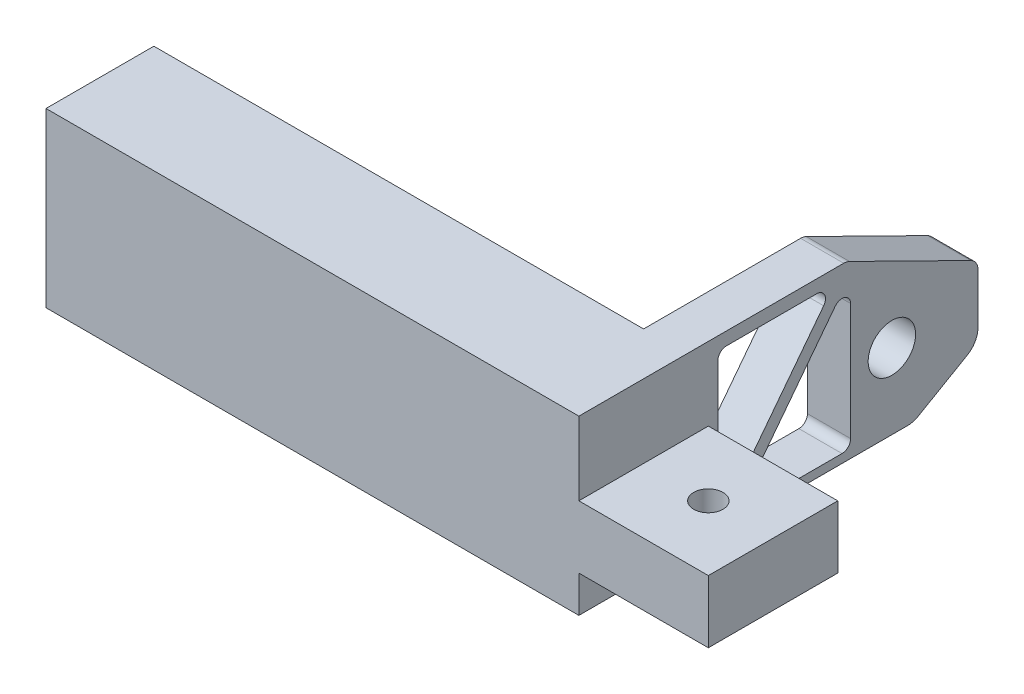
SolidWorks part; units mm, degrees
material "PLA"
ref_plane "Front Plane" through (0, 0, 0) normal (0, 0, 1) x (1, 0, 0)
ref_plane "Top Plane" through (0, 0, 0) normal (0, 1, 0) x (1, 0, 0)
ref_plane "Right Plane" through (0, 0, 0) normal (1, 0, 0) x (0, 0, -1)
sketch "Sketch1" plane through (0, 0, 0) normal (1, 0, 0) x (0, 0, -1)
  line L1 (-35.9146, 20.1296) -> (56.5854, 20.1296)
  line L2 (-35.9146, 20.1296) -> (-35.9146, -19.8704)
  line L3 (-35.9146, -19.8704) -> (56.5854, -19.8704)
  line L4 (56.5854, 20.1296) -> (56.5854, -19.8704)
  dimension "D1" = 92.5
  dimension "D2" = 40
extrude "Boss-Extrude1" add sketch "Sketch1" along normal blind 10
sketch "Sketch4" plane through (0, 0, 0) normal (-1, 0, 0) x (0, 0, 1)
  line L11 (-56.5854, 20.1296) -> (35.9146, 20.1296) construction
  line L12 (10.9146, 20.1296) -> (35.9146, 20.1296)
  line L13 (10.9146, 20.1296) -> (10.9146, -19.8704)
  line L14 (10.9146, -19.8704) -> (35.9146, -19.8704)
  line L15 (35.9146, 20.1296) -> (35.9146, -19.8704)
  line L16 (10.9146, 20.1296) -> (35.9146, -19.8704) construction
  line L17 (10.9146, -19.8704) -> (35.9146, 20.1296) construction
  line L18 (18.4146, 12.6296) -> (18.4146, -12.3704)
  line L19 (18.4146, -12.3704) -> (28.4146, -12.3704)
  line L20 (28.4146, 12.6296) -> (28.4146, -12.3704)
  line L21 (18.4146, 12.6296) -> (28.4146, 12.6296)
  point P4 (23.4146, 0.1296)
  dimension "D1" = 25
  dimension "D2" = 7.5
sketch "Sketch5" plane through (0, 0, 0) normal (-1, 0, 0) x (0, 0, 1)
  line L0 (35.9146, -19.8704) -> (-56.5854, -19.8704) construction
  line L2 (35.9146, 20.1296) -> (35.9146, -19.8704) construction
  circle A0 centre (-36.6254, -2.4304) radius 5.5
  dimension "D1" = 11
  dimension "D2" = 17.44
  dimension "D3" = 72.54
extrude "Cut-Extrude1" cut sketch "Sketch5" against normal blind 27
sketch "Sketch6" plane through (10, 0, 0) normal (1, 0, 0) x (0, 0, -1)
  line L0 (-35.9146, 20.1296) -> (-35.9146, -19.8704) construction
  line L1 (-5.9146, -2.8704) -> (-35.9146, -2.8704)
  line L2 (-5.9146, -2.8704) -> (-5.9146, 3.1296)
  line L3 (-5.9146, 3.1296) -> (-35.9146, 3.1296)
  line L4 (-35.9146, -2.8704) -> (-35.9146, 3.1296)
  line L5 (-5.9146, -2.8704) -> (-35.9146, 3.1296) construction
  line L6 (-5.9146, 3.1296) -> (-35.9146, -2.8704) construction
  line L8 (-35.9146, -19.8704) -> (56.5854, -19.8704) construction
  point P0 (-20.9146, 0.1296)
  dimension "D1" = 30
  dimension "D2" = 6
  dimension "D3" = 20
extrude "Boss-Extrude5" add sketch "Sketch6" along normal blind 30
sketch "Sketch7" plane through (0, -2.8704, 0) normal (0, -1, 0) x (1, 0, 0)
  line L1 (40, 35.9146) -> (10, 35.9146)
  line L2 (40, 35.9146) -> (40, 5.9146)
  line L3 (40, 5.9146) -> (10, 5.9146)
  line L4 (10, 35.9146) -> (10, 5.9146)
extrude "Boss-Extrude6" add sketch "Sketch7" along normal blind 8.5
extrude "Boss-Extrude7" add sketch "Sketch4" along normal blind 113.5
fillet "Fillet1" radius 3 4 edges at (-113.5, -12.3704, 23.4146) (-113.5, 0.1296, 28.4146) (-113.5, 12.6296, 23.4146) (-113.5, 0.1296, 18.4146)
chamfer "Chamfer1" distance 15 angle 63.75 1 edges at (5, 20.1296, -56.5854)
fillet "Fillet3" radius 3 2 edges at (5, 20.1296, -26.1684) (5, 5.1296, -56.5854)
chamfer "Chamfer3" distance 15 angle 30 1 edges at (5, -19.8704, -56.5854)
fillet "Fillet7" radius 5 2 edges at (5, -19.8704, -41.5854) (5, -11.2102, -56.5854)
sketch "Sketch9" plane through (10, 0, 0) normal (1, 0, 0) x (0, 0, -1)
  line L0 (-3.7146, 17.1296) -> (23.2854, 17.1296)
  line L1 (23.2854, 17.1296) -> (-3.7146, -18.0471)
  line L2 (-3.7146, -18.0471) -> (-3.7146, 17.1296)
  line L3 (0.2028, -17.8704) -> (27.0672, 17.1296)
  line L4 (27.0672, 17.1296) -> (27.0672, -17.8704)
  line L5 (27.0672, -17.8704) -> (0.2028, -17.8704)
  line L6 (25.4689, 20.1296) -> (-35.9146, 20.1296) construction
  line L7 (-5.9146, -11.3704) -> (-5.9146, 3.1296) construction
  line L8 (-35.9146, -19.8704) -> (40.2456, -19.8704) construction
  dimension "D1" = 27
  dimension "D2" = 3
  dimension "D3" = 2.2
  dimension "D4" = 2
  dimension "D5" = 3
  dimension "D6" = 35
extrude "Cut-Extrude3" cut sketch "Sketch9" against normal through all
fillet "Fillet8" radius 2 3 edges at (5, -18.0471, 3.7146) (5, 17.1296, -23.2854) (5, 17.1296, 3.7146)
fillet "Fillet9" radius 2 3 edges at (5, 17.1296, -27.0672) (5, -17.8704, -27.0672) (5, -17.8704, -0.2028)
sketch "Sketch10" plane through (0, 3.1296, 0) normal (0, 1, 0) x (1, 0, 0)
  line L0 (40, -5.9146) -> (10, -35.9146) construction
  line L1 (40, -35.9146) -> (10, -5.9146) construction
  point P10 (25, -20.9146)
hole_wizard "M8 Tapped Hole1" positions "Sketch10" profile "Sketch11" tap size "M8" standard "ISO"
sketch "Sketch11" plane through (25, 3.1296, 20.9146) normal (1, 0, 0) x (0, 0, 1)
  line L0 (0, 0) -> (0, 24.2929)
  line L1 (0, 24.2929) -> (3.4, 22.25)
  line L2 (3.4, 22.25) -> (3.4, 0)
  line L5 (3.4, 0) -> (0, 0)
  line L10 (0, 24.2929) -> (-3.4, 22.25) construction
  line L11 (0, -6.35) -> (0, 107.95) construction
  dimension "Tap Drill Dia." = 6.8
  dimension "Tap Drill Depth" = 22.25
  dimension "Drill Angle" = 118
cosmetic thread "Hole Thread1" parameters "D1"=16, "D2"=8
